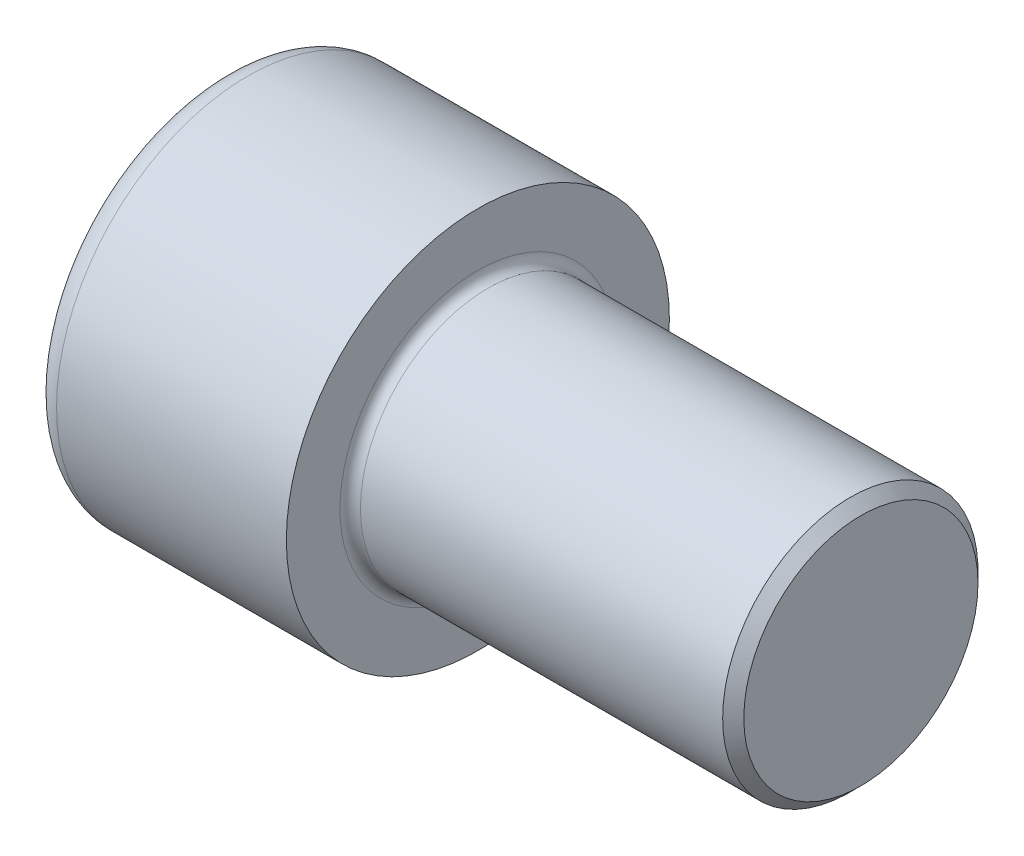
SolidWorks part; units mm, degrees
revolve "Base-Revolve" add sketch "BodySke"
sketch "BodySke" plane through (0, 0, 0) normal (0, 0, 1) x (1, 0, 0)
  line L0 (0, 0) -> (0, 15)
  line L1 (0, 15) -> (20, 15)
  line L2 (20, 15) -> (20, 10)
  line L3 (20, 10) -> (49.172, 10)
  line L4 (50, 9.172) -> (50, 0)
  line L5 (50, 0) -> (0, 0)
  line L6 (-31.75, 0) -> (127, 0) construction
  line L8 (50, 9.172) -> (49.172, 10)
  line L10 (50, -9.172) -> (49.172, -10) construction
  line L11 (21.5, 9.525) -> (21.5, 3.175) construction
  line L12 (20, 9.525) -> (20, 3.175) construction
  line L13 (-10, 9.525) -> (-10, 3.175) construction
  dimension "Body_ch_ang" = 45
  dimension "Thread_length" = 60
cosmetic thread "ThreadCosmetic" [suppressed]
fillet "Fillet1" radius 0.8 1 edges at (20, 0, 10)
fillet "Fillet2" radius 2 1 edges at (0, 0, 15)
ref_plane "Plane1" through (0, 0, 0) normal (0, 0, 1) x (1, 0, 0)
ref_plane "Plane2" through (0, 0, 0) normal (0, 1, 0) x (1, 0, 0)
ref_plane "Plane3" through (0, 0, 0) normal (1, 0, 0) x (0, 0, -1)
other "Configuration Table"
sketch "Sketch2" plane through (0, 0, 0) normal (0, 0, 1) x (1, 0, 0)
  line L0 (0, 8.525) -> (10, 8.525)
  line L1 (10, 8.525) -> (14.9219, 0)
  line L2 (-31.75, 0) -> (127, 0) construction
  line L3 (14.9219, 0) -> (0, 0)
  line L4 (0, 0) -> (0, 8.525)
  line L6 (0, 0) -> (47.625, 0) construction
  dimension "D2" = 60
revolve "Hex-PreBroach" cut sketch "Sketch2" angle 360 about L6
sketch "Sketch3" plane through (0, 0, 0) normal (-1, 0, 0) x (0, 0.5, 0.866)
  line L0 (4.9219, 8.525) -> (-4.9219, 8.525)
  line L1 (-4.9219, 8.525) -> (-9.8438, 0)
  line L2 (4.9219, 8.525) -> (9.8438, 0)
  line L3 (4.9219, -8.525) -> (9.8438, 0)
  line L4 (4.9219, -8.525) -> (-4.9219, -8.525)
  line L5 (-4.9219, -8.525) -> (-9.8438, 0)
extrude "Hex" cut sketch "Sketch3" against normal blind 10
sketch "ThdSchSke" plane through (0, 0, 0) normal (0, 0, 1) x (1, 0, 0)
  line L0 (24.5, -9.172) -> (23.9202, -10)
  line L1 (24.5, -9.172) -> (25.0798, -10)
  line L2 (25.0798, -10) -> (25.0798, -12.5)
  line L3 (-3.175, 0) -> (5.1513, 0) construction
  line L4 (0, 13) -> (0, -13) construction
  line L5 (25.0798, -12.5) -> (23.9202, -12.5)
  line L6 (23.9202, -12.5) -> (23.9202, -10)
revolve "ThreadSchematic" [suppressed] cut sketch "ThdSchSke" angle 360 about L3
pattern_linear "ThdSchPat" [suppressed]
equation "\"D2@Sketch3\" = \"Hex_size@Sketch3\" / 2"
equation "\"D1@Sketch3\" = \"Hex_size@Sketch3\" / 2"
equation "\"D1@Sketch2\" = \"Hex_size@Sketch3\" / 2"
equation "\"Thread_minor@ThreadCosmetic\"  =  \"Minor_dia@BodySke\""
equation "\"Depth@Sketch2\" =  \"Key_eng@Hex\""
equation "\"Thread_length@ThreadCosmetic\" = ((sgn( (\"Length@BodySke\" - \"Advance@BodySke\" * 3.0) - \"Thread_nom@BodySke\" )-1)*( (\"Length@BodySke\" - \"Advance@BodySke\" * 3.0) - \"Thread_nom@BodySke\" ))/-2+ \"Thread_nom@BodySke\""
equation "\"Thread_minor@ThdSchSke\" = \"Minor_dia@BodySke\""
equation "\"Diameter@ThdSchSke\" = \"Diameter@BodySke\""
equation "\"Overcut@ThdSchSke\" = \"Diameter@BodySke\" * 1.25"
equation "\"Start@ThdSchSke\" = \"Head_ht@BodySke\" + \"Length@BodySke\" - \"Thread_length@ThreadCosmetic\"  '---Non-countersunk---"
equation "\"Num_threads@ThdSchPat\" = int( \"Thread_length@ThreadCosmetic\" / \"Advance@BodySke\" + 0.999 )  + 1"
equation "\"Advance@ThdSchPat\" = \"Thread_length@ThreadCosmetic\" /  (\"Num_threads@ThdSchPat\" - 1) 'relax it"
equation "\"Num_threads@ThdSchPat\" = \"Num_threads@ThdSchPat\" - sgn( \"Num_threads@ThdSchPat\" - 1) '---chamfered tips only---"
